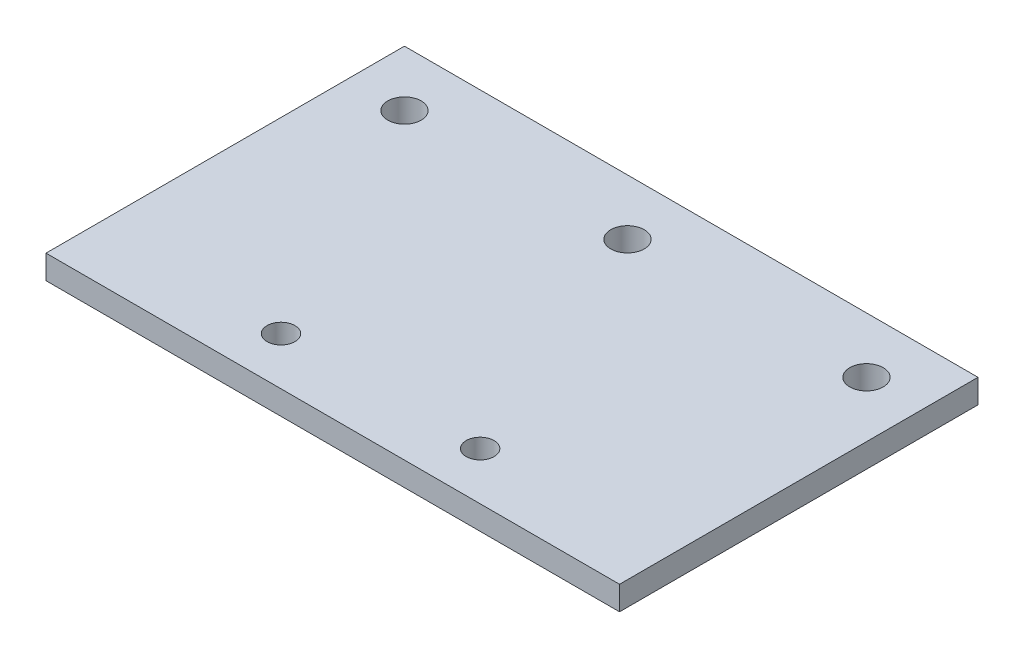
SolidWorks part; units mm, degrees
ref_plane "Front Plane" through (0, 0, 0) normal (0, 0, 1) x (1, 0, 0)
ref_plane "Top Plane" through (0, 0, 0) normal (0, 1, 0) x (1, 0, 0)
ref_plane "Right Plane" through (0, 0, 0) normal (1, 0, 0) x (0, 0, -1)
sketch "Sketch1" plane through (0, 0, 0) normal (0, 1, 0) x (1, 0, 0)
  line L0 (0, 0) -> (72, 0)
  line L1 (72, 0) -> (72, -45)
  line L2 (72, -45) -> (0, -45)
  line L3 (0, -45) -> (0, 0)
  circle A0 centre (7, -7) radius 2.1
  circle A1 centre (35, -7) radius 2.1
  circle A2 centre (65, -7) radius 2.1
  circle A3 centre (23.5, -39) radius 1.75
  circle A4 centre (48.5, -39) radius 1.75
  circle A5 centre (23.5, -39) radius 1.75 construction
  circle A6 centre (48.5, -39) radius 1.75 construction
  dimension "D3" = 4.2
  dimension "D4" = 7
  dimension "D1" = 72
  dimension "D2" = 45
  dimension "D5" = 28
  dimension "D6" = 7
  dimension "D7" = 7
extrude "Boss-Extrude1" add sketch "Sketch1" along normal blind 3
